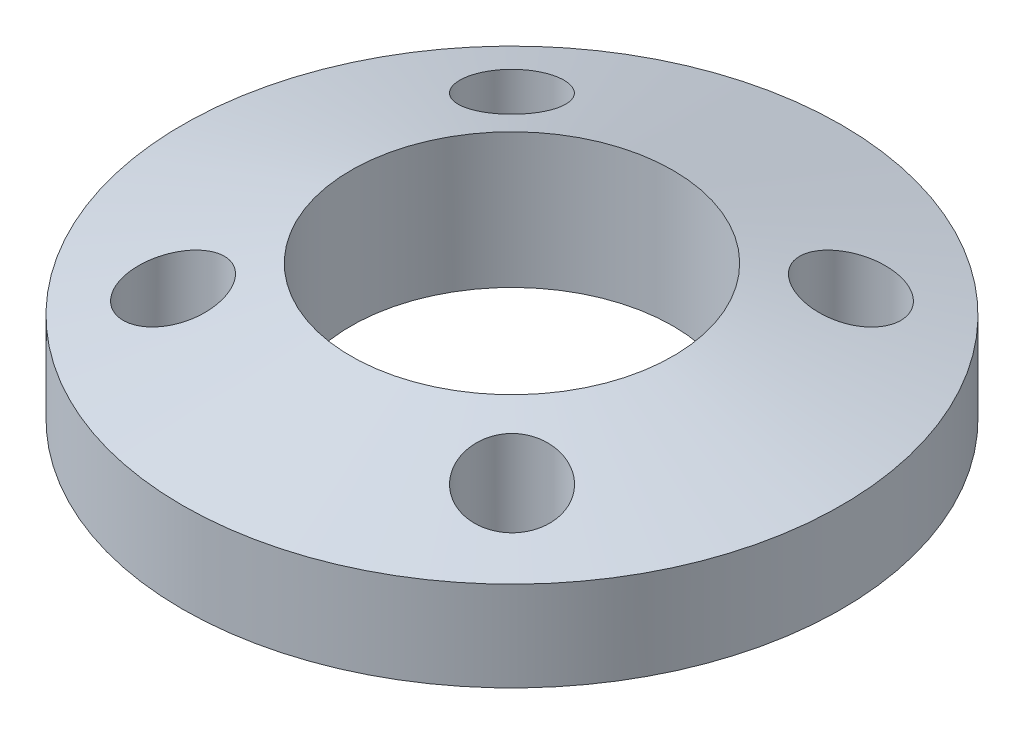
SolidWorks part; units mm, degrees
ref_plane "Front Plane" through (0, 0, 0) normal (0, 0, 1) x (1, 0, 0)
ref_plane "Top Plane" through (0, 0, 0) normal (0, 1, 0) x (1, 0, 0)
ref_plane "Right Plane" through (0, 0, 0) normal (1, 0, 0) x (0, 0, -1)
sketch "Sketch1" plane through (0, 0, 0) normal (0, 1, 0) x (1, 0, 0)
  line L1 (-5.6577, 5.656) -> (5.6577, 5.656) construction
  line L2 (-5.6577, 5.656) -> (-5.6577, -5.656) construction
  line L3 (-5.6577, -5.656) -> (5.6577, -5.656) construction
  line L4 (5.6577, 5.656) -> (5.6577, -5.656) construction
  circle A0 centre (0, 0) radius 11
  circle A1 centre (0, 0) radius 5.375
  circle A2 centre (-5.6577, -5.656) radius 1.475
  circle A3 centre (-5.6577, 5.656) radius 1.475
  circle A4 centre (5.6577, 5.656) radius 1.475
  circle A5 centre (5.6577, -5.656) radius 1.475
  point P16 (0, 5.656)
  point P17 (5.6577, 0)
  dimension "D1" = 10.75
  dimension "D2" = 22
  dimension "D3" = 2.95
  dimension "D4" = 16
  dimension "D5" = 11.3154
extrude "Boss-Extrude1" add sketch "Sketch1" along normal blind 3
ref_plane "Plane1" through (0, 5, 0) normal (0, 1, 0) x (1, 0, 0)
sketch "Sketch5" plane through (0, 0, 0) normal (1, 0, 0) x (0, 0, -1)
  line L0 (-10.9914, 3) -> (11, 3)
  line L1 (11, 3) -> (-11, 3) construction
  line L2 (0, 0) -> (0, 9.6315) construction
  line L3 (5.375, 4.5) -> (11, 3)
  line L5 (5.375, 3) -> (5.375, 4.5)
  line L6 (5.375, 3) -> (11, 3)
  dimension "D1" = 1.5
  dimension "D2" = 5.375
revolve "Revolve1" add sketch "Sketch5" angle 360 about L2
sketch "Sketch6" plane through (0, 0, 0) normal (0, -1, 0) x (1, 0, 0)
  circle A0 centre (-5.6577, 5.656) radius 1.475
  circle A1 centre (-5.6577, -5.656) radius 1.475
  circle A2 centre (5.6577, 5.656) radius 1.475
  circle A3 centre (5.6577, -5.656) radius 1.475
  dimension "D1" = 2.95
extrude "Cut-Extrude1" cut sketch "Sketch6" against normal blind 11
